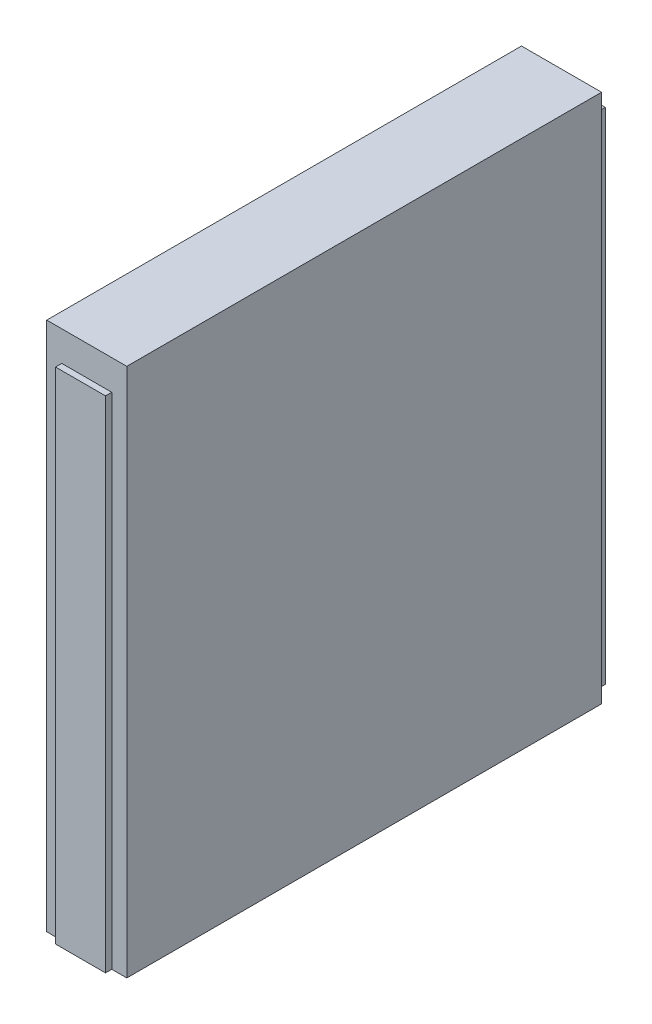
SolidWorks part; units mm, degrees
other "COLL.BOX-Estrusione-Estrusione3"
ref_plane "Piano frontale" through (0, 0, 0) normal (0, 0, 1) x (1, 0, 0)
ref_plane "Piano superiore" through (0, 0, 0) normal (0, 1, 0) x (1, 0, 0)
ref_plane "Piano destro" through (0, 0, 0) normal (1, 0, 0) x (0, 0, -1)
sketch "Schizzo1" plane through (0, 0, 0) normal (0, 0, 1) x (1, 0, 0)
  line L1 (-20, 200) -> (20, 200)
  line L2 (-20, 200) -> (-20, -200)
  line L3 (-20, -200) -> (20, -200)
  line L4 (20, 200) -> (20, -200)
  line L5 (-20, 200) -> (20, -200) construction
  line L6 (-20, -200) -> (20, 200) construction
  point P0 (0, 0)
  dimension "D1" = 40
  dimension "D2" = 400
extrude "Estrusione-Estrusione1" add sketch "Schizzo1" along normal blind 400
sketch "Schizzo4" plane through (0, -200, 0) normal (0, -1, 0) x (-1, 0, 0)
  line L0 (20, -400) -> (-20, -400) construction
  line L1 (32.0333, -395) -> (-32.0333, -395)
  line L2 (32.0333, -395) -> (32.0333, -15)
  line L3 (32.0333, -15) -> (-32.0333, -15)
  line L4 (-32.0333, -395) -> (-32.0333, -15)
  line L5 (32.0333, -395) -> (-32.0333, -15) construction
  line L6 (32.0333, -15) -> (-32.0333, -395) construction
  point P0 (0, -205)
  point P5 (0, -211.1604)
  point P8 (0, -211.1604)
  dimension "D1" = 195
  dimension "D3" = 380
extrude "Estrusione-Estrusione3" add sketch "Schizzo4" against normal blind 424 separate body
